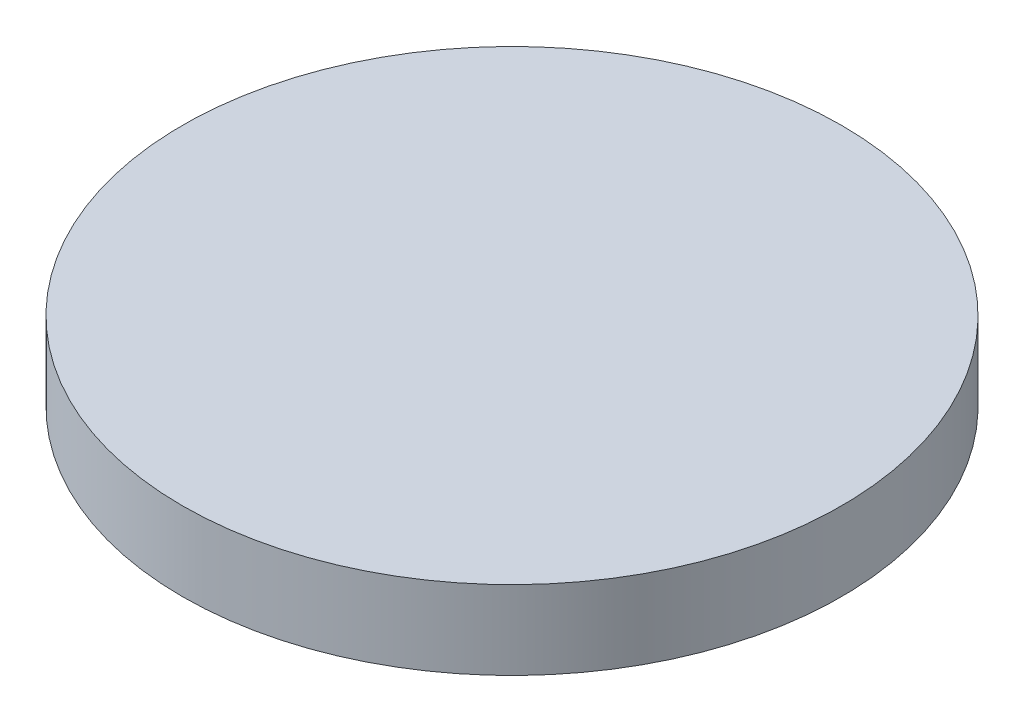
SolidWorks part; units mm, degrees
material "ABS"
ref_plane "Front Plane" through (0, 0, 0) normal (0, 0, 1) x (1, 0, 0)
ref_plane "Top Plane" through (0, 0, 0) normal (0, 1, 0) x (1, 0, 0)
ref_plane "Right Plane" through (0, 0, 0) normal (1, 0, 0) x (0, 0, -1)
sketch "Sketch1" plane through (0, 0, 0) normal (0, 1, 0) x (1, 0, 0)
  circle A0 centre (0, 0) radius 42.545
  dimension "D1" = 85.09
extrude "Boss-Extrude1" add sketch "Sketch1" along normal blind 10.16
shell "Shell1" thickness 1.27
